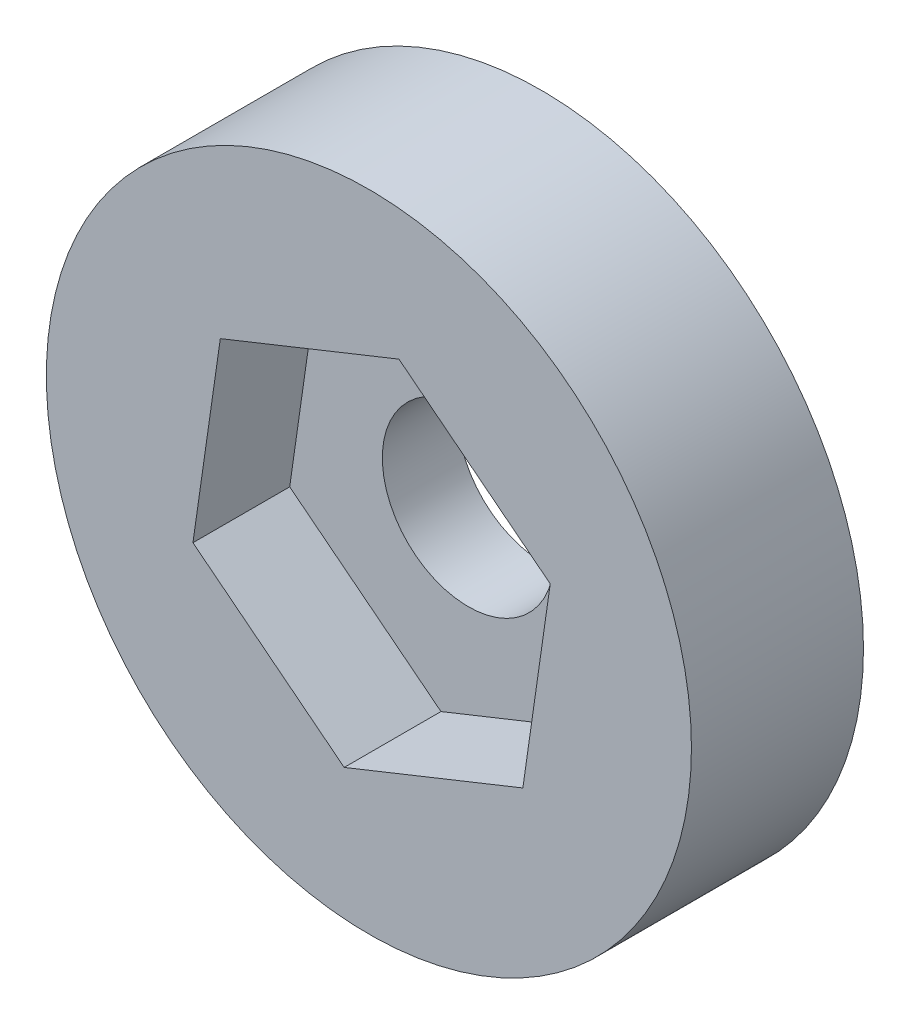
SolidWorks part; units mm, degrees
ref_plane "Front Plane" through (0, 0, 0) normal (0, 0, 1) x (1, 0, 0)
ref_plane "Top Plane" through (0, 0, 0) normal (0, 1, 0) x (1, 0, 0)
ref_plane "Right Plane" through (0, 0, 0) normal (1, 0, 0) x (0, 0, -1)
sketch "Sketch1" plane through (0, 0, 0) normal (0, 0, 1) x (1, 0, 0)
  circle A0 centre (58.8, 0) radius 6
extrude "Boss-Extrude1" add sketch "Sketch1" along normal blind 3.2
sketch "Sketch2" plane through (0, 0, 3.2) normal (0, 0, 1) x (1, 0, 0)
  line L1 (59.3592, 3.5432) -> (56.0362, 2.2126)
  line L2 (56.0362, 2.2126) -> (55.5269, -1.3306)
  line L3 (55.5269, -1.3306) -> (58.3408, -3.5432)
  line L4 (58.3408, -3.5432) -> (61.6638, -2.2126)
  line L5 (61.6638, -2.2126) -> (62.1731, 1.3306)
  line L6 (62.1731, 1.3306) -> (59.3592, 3.5432)
  circle A0 centre (58.85, 0) radius 3.1 construction
  dimension "D1" = 6.2
extrude "Cut-Extrude1" cut sketch "Sketch2" against normal blind 1.8
sketch "Sketch3" plane through (0, 0, 1.4) normal (0, 0, 1) x (1, 0, 0)
  circle A0 centre (58.85, 0) radius 1.6
extrude "Cut-Extrude2" cut sketch "Sketch3" against normal blind 3.8
